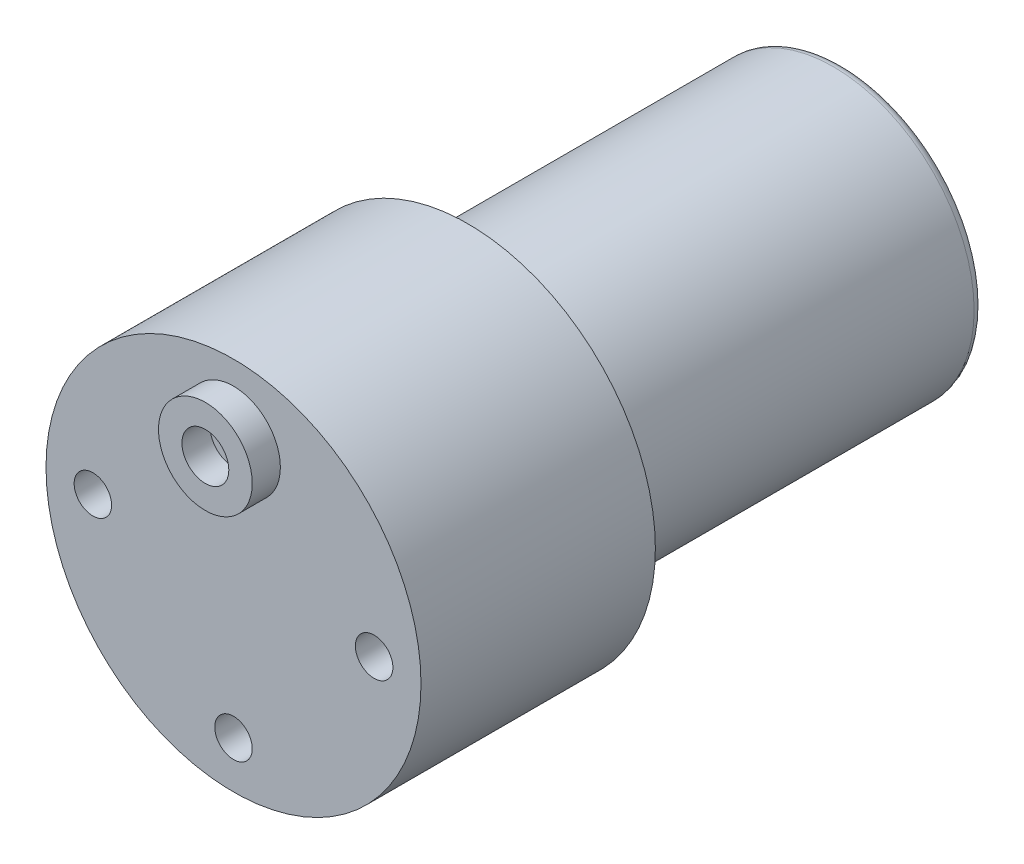
SolidWorks part; units mm, degrees
ref_plane "Alzado" through (0, 0, 0) normal (0, 0, 1) x (1, 0, 0)
ref_plane "Planta" through (0, 0, 0) normal (0, 1, 0) x (1, 0, 0)
ref_plane "Vista lateral" through (0, 0, 0) normal (1, 0, 0) x (0, 0, -1)
sketch "Croquis1" plane through (0, 0, 0) normal (0, 0, 1) x (1, 0, 0)
  circle A0 centre (0, 0) radius 15
extrude "Saliente-Extruir1" add sketch "Croquis1" along normal blind 40
sketch "Croquis2" plane through (0, 0, 40) normal (0, 0, 1) x (1, 0, 0)
  circle A0 centre (0, 0) radius 20
extrude "Saliente-Extruir2" add sketch "Croquis2" along normal blind 25
sketch "Croquis3" plane through (0, 0, 0) normal (0, 0, -1) x (-1, 0, 0)
  circle A0 centre (0, 0) radius 0.8845
extrude "Saliente-Extruir3" add sketch "Croquis3" along normal blind 3
sketch "Croquis4" plane through (0, 0, 65) normal (0, 0, 1) x (1, 0, 0)
  circle A1 centre (0, 12.5) radius 5
  circle A2 centre (0, 12.5) radius 2.5
extrude "Saliente-Extruir4" add sketch "Croquis4" along normal blind 3
sketch "Croquis5" plane through (0, 0, 0) normal (0, 0, -1) x (-1, 0, 0)
  line L0 (8.6033, 0) -> (11.5059, 0) construction
  line L1 (-8.6033, 0) -> (-11.5059, 0) construction
  line L2 (0, -11.5059) -> (0, -8.6033) construction
  line L3 (-8.0631, -3.0004) -> (-10.7835, -4.0127) construction
  line L4 (3.0004, -8.0631) -> (4.0127, -10.7835) construction
  line L5 (7.8978, 3.4118) -> (10.5624, 4.5629) construction
  line L6 (-3.1492, 8.0062) -> (-4.2117, 10.7073) construction
  line L7 (-8.0631, -3.0004) -> (-10.7835, -4.0127)
  line L8 (0, -8.6033) -> (0, -11.5059)
  line L9 (3.1069, -8.0227) -> (4.0127, -10.7835)
  line L10 (8.6033, 0) -> (11.5059, 0)
  line L11 (7.8978, 3.4118) -> (10.5624, 4.5629)
  line L12 (0, 8.6033) -> (0, 11.5059)
  line L13 (-3.1492, 8.0062) -> (-4.2117, 10.7073)
  line L14 (-8.6033, 0) -> (-11.5059, 0)
  line L15 (-8.0631, -3.0004) -> (-10.7835, -4.0127)
  line L16 (0, 8.6033) -> (0, 11.5059) construction
  arc A0 (10.5624, 4.5629) -> (0, 11.5059) centre (0, 0) ccw
  arc A1 (7.8978, 3.4118) -> (0, 8.6033) centre (0, 0) ccw
  arc A2 (-3.1492, 8.0062) -> (-8.6033, 0) centre (0, 0) ccw
  arc A3 (-4.2117, 10.7073) -> (-11.5059, 0) centre (0, 0) ccw
  arc A4 (-8.0631, -3.0004) -> (0, -8.6033) centre (0, 0) ccw
  arc A5 (-10.7835, -4.0127) -> (0, -11.5059) centre (0, 0) ccw
  arc A6 (3.0004, -8.0631) -> (8.6033, 0) centre (0, 0) ccw
  arc A7 (4.0127, -10.7835) -> (11.5059, 0) centre (0, 0) ccw
extrude "Cortar-Extruir1" cut sketch "Croquis5" against normal blind 3 contours L13 A3 L14 A2 | L7 A5 L8 A4 | L9 A7 L10 A6 | A1 L11 A0 L12
fillet "Redondeo3" radius 1 1 edges at (15, 0, 0)
sketch "Croquis6" plane through (0, 0, 65) normal (0, 0, 1) x (1, 0, 0)
  circle A1 centre (15, 0) radius 2
  circle A2 centre (-15, 0) radius 2
  circle A3 centre (0, -15) radius 2
extrude "Cortar-Extruir2" cut sketch "Croquis6" against normal blind 10
sketch "Croquis7" plane through (0, 0, 65) normal (0, 0, 1) x (1, 0, 0)
  line L0 (0, 12.5) -> (0, 15) construction
  circle A0 centre (0, 12.5) radius 2.5 construction
  dimension "D1" = 2.5
